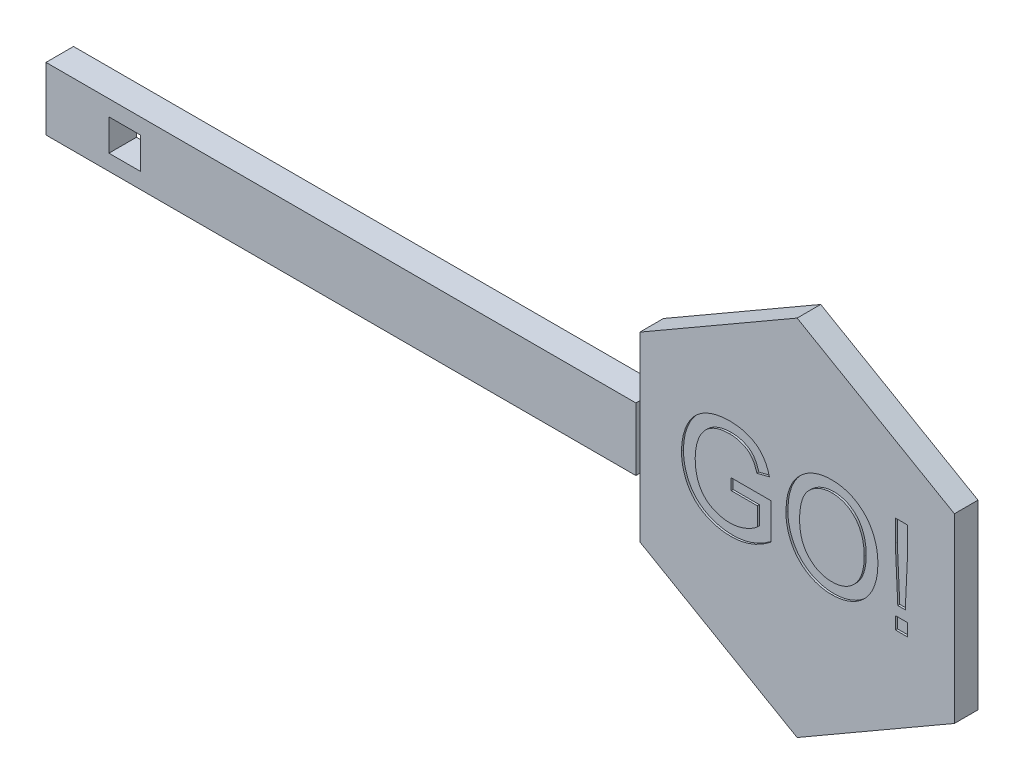
SolidWorks part; units mm, degrees
material "ABS PC"
ref_plane "Front Plane" through (0, 0, 0) normal (0, 0, 1) x (1, 0, 0)
ref_plane "Top Plane" through (0, 0, 0) normal (0, 1, 0) x (1, 0, 0)
ref_plane "Right Plane" through (0, 0, 0) normal (1, 0, 0) x (0, 0, -1)
sketch "Sketch1" plane through (0, 0, 0) normal (0, 0, 1) x (1, 0, 0)
  line L1 (-10, -4) -> (65, -4)
  line L2 (-10, -4) -> (-10, 4)
  line L3 (-10, 4) -> (65, 4)
  line L4 (65, -4) -> (65, 4)
  point P4 (-10, 0)
  dimension "D1" = 75
  dimension "D2" = 8
  dimension "D3" = 10
extrude "Arm" add sketch "Sketch1" along normal blind 3.5
sketch "Sketch2" plane through (0, 0, 0) normal (0, 0, 1) x (1, 0, 0)
  line L0 (65, -4) -> (65, 4) construction
  line L1 (85, -23.094) -> (105, -11.547)
  line L2 (105, -11.547) -> (105, 11.547)
  line L3 (105, 11.547) -> (85, 23.094)
  line L4 (85, 23.094) -> (65, 11.547)
  line L5 (65, 11.547) -> (65, -11.547)
  line L6 (65, -11.547) -> (85, -23.094)
  circle A0 centre (85, 0) radius 20 construction
  dimension "D1" = 40
extrude "Hex Sign" add sketch "Sketch2" along normal blind 3
sketch "Sketch3" plane through (0, 0, 3) normal (0, 0, 1) x (1, 0, 0)
  line L0 (65, -5) -> (105, -5) construction
  text T0 "GO!" font "Arial" height in points 48
  dimension "D1" = 40
  dimension "D2" = 20
  dimension "D3" = 5
extrude "GO Text" cut sketch "Sketch3" against normal blind 0.25
sketch "Sketch4" plane through (0, 0, 3.5) normal (0, 0, 1) x (1, 0, 0)
  line L1 (-2, 2) -> (2, 2)
  line L2 (-2, 2) -> (-2, -2)
  line L3 (-2, -2) -> (2, -2)
  line L4 (2, 2) -> (2, -2)
  line L5 (-2, 2) -> (2, -2) construction
  line L6 (-2, -2) -> (2, 2) construction
  point P0 (0, 0)
  dimension "D1" = 4
  dimension "D2" = 4
extrude "Arm Square" cut sketch "Sketch4" against normal through all
equation "\"D2@Sketch4\"=\"D1@Sketch4\""
